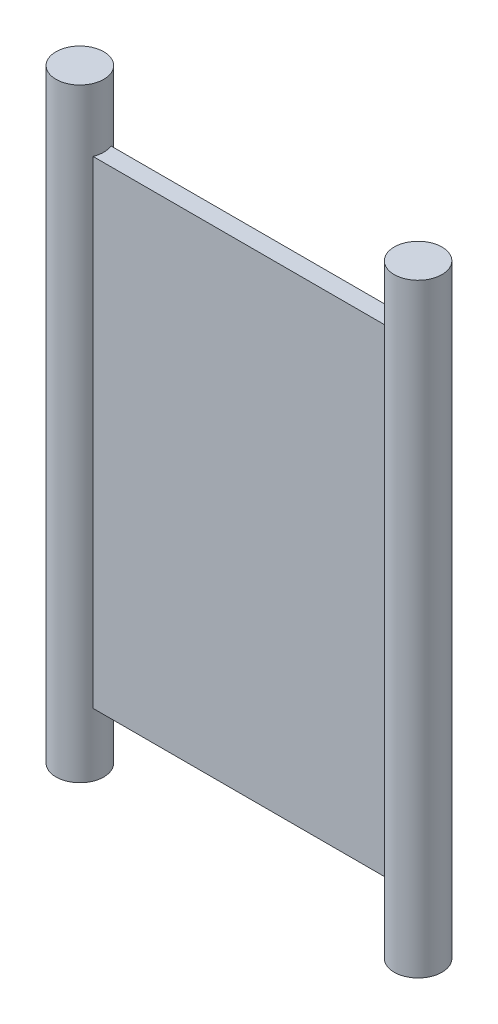
SolidWorks part; units mm, degrees
ref_plane "Front Plane" through (0, 0, 0) normal (0, 0, 1) x (1, 0, 0)
ref_plane "Top Plane" through (0, 0, 0) normal (0, 1, 0) x (1, 0, 0)
ref_plane "Right Plane" through (0, 0, 0) normal (1, 0, 0) x (0, 0, -1)
sketch "Sketch1" plane through (0, 0, 0) normal (0, 1, 0) x (1, 0, 0)
  line L1 (9.375, 0.5) -> (-9.375, 0.5)
  line L2 (9.375, 0.5) -> (9.375, -0.5)
  line L3 (9.375, -0.5) -> (-9.375, -0.5)
  line L4 (-9.375, 0.5) -> (-9.375, -0.5)
  line L5 (9.375, 0.5) -> (-9.375, -0.5) construction
  line L6 (9.375, -0.5) -> (-9.375, 0.5) construction
  point P0 (0, 0)
  dimension "D1" = 18.75
  dimension "D3" = 1
extrude "Boss-Extrude1" add sketch "Sketch1" along normal blind 26.5
ref_plane "Plane1" through (0, 13.25, 0) normal (0, 1, 0) x (1, 0, 0)
sketch "Sketch2" plane through (0, 13.25, 0) normal (0, 1, 0) x (1, 0, 0)
  line L0 (9.375, -0.5) -> (9.375, 0.5) construction
  line L1 (-9.375, 0.5) -> (-9.375, -0.5) construction
  line L2 (9.375, -0.5) -> (9.375, 0.5) construction
  line L3 (-9.375, 0.5) -> (-9.375, -0.5) construction
  circle A0 centre (-9.375, 0) radius 1.325
  circle A1 centre (9.375, 0) radius 1.325
  dimension "D1" = 2.65
extrude "Boss-Extrude2" add sketch "Sketch2" along normal mid plane 33.5
